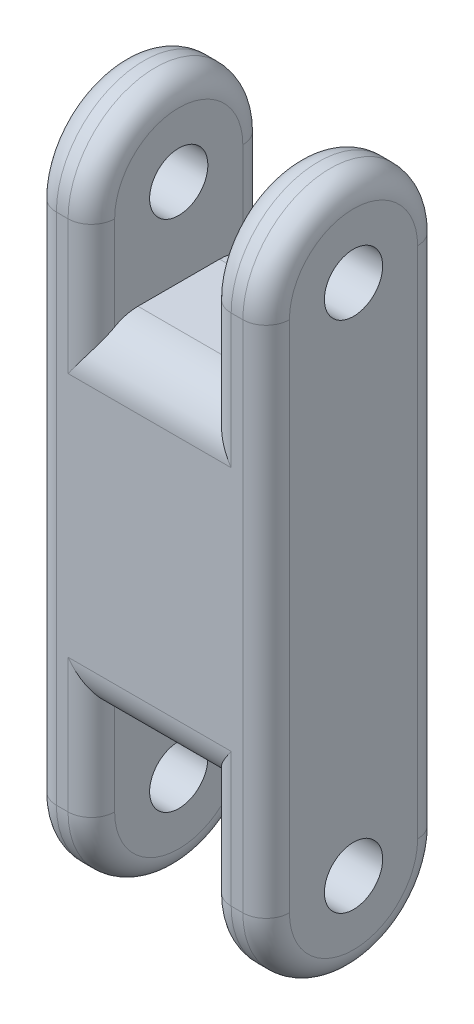
SolidWorks part; units mm, degrees
material "ABS"
ref_plane "Front" through (0, 0, 0) normal (0, 0, 1) x (1, 0, 0)
ref_plane "Top" through (0, 0, 0) normal (0, 1, 0) x (1, 0, 0)
ref_plane "Right" through (0, 0, 0) normal (1, 0, 0) x (0, 0, -1)
sketch "Sketch1" plane through (0, 0, 0) normal (1, 0, 0) x (0, 0, -1)
  line L0 (-4.7625, 0) -> (-4.7625, 27.9908)
  line L1 (4.7625, 27.9908) -> (4.7625, 0)
  arc A0 (-4.7625, 27.9908) -> (4.7625, 27.9908) centre (0, 27.9908) cw
  arc A1 (4.7625, 0) -> (-4.7625, 0) centre (0, 0) cw
  dimension "D1" = 9.525
  dimension "D2" = 27.9908
extrude "Boss-Extrude1" add sketch "Sketch1" along normal blind 12.7
sketch "Sketch2" plane through (12.7, 0, 0) normal (1, 0, 0) x (0, 0, -1)
  circle A0 centre (0, 0) radius 1.5875
  circle A1 centre (0, 27.9908) radius 1.5875
  dimension "D1" = 3.175
extrude "Cut-Extrude1" cut sketch "Sketch2" against normal blind 19.05
sketch3d "3DSketch1"
  line L0 (6.35, 27.9908, -4.7625) -> (6.35, 23.2283, -4.7625)
  line L1 (12.7, 27.9908, -4.7625) -> (0, 27.9908, -4.7625) construction
  line L2 (12.7, 27.9908, 4.7625) -> (0, 27.9908, 4.7625) construction
  line L3 (6.35, 27.9908, 4.7625) -> (6.35, 23.2283, 4.7625)
  line L5 (6.35, 0, 4.7625) -> (6.35, 4.7625, 4.7625)
  line L7 (12.7, 0, 4.7625) -> (0, 0, 4.7625) construction
  line L8 (12.7, 0, -4.7625) -> (0, 0, -4.7625) construction
  line L9 (6.35, 0, -4.7625) -> (6.35, 4.7625, -4.7625)
  line L10 (6.35, 23.2283, -4.7625) -> (6.35, 23.2283, 4.7625)
  line L11 (6.35, 4.7625, -4.7625) -> (6.35, 4.7625, 4.7625)
  arc A0 (6.35, 27.9908, -4.7625) -> (6.35, 27.9908, 4.7625) centre (6.35, 27.9908, 0) ccw
  arc A2 (6.35, 0, 4.7625) -> (6.35, 0, -4.7625) centre (6.35, 0, 0) ccw
  point P6 (11.1125, 27.9908, 0)
  point P18 (11.1125, 0, 0)
  dimension "D1" = 4.7625
  dimension "D2" = 4.7625
extrude "Cut-Extrude2" cut sketch "3DSketch1" along direction (-1, 0, 0) on the side against the normal mid plane 6.35
fillet "Fillet2" radius 2.54 4 edges
fillet "Fillet3" radius 1.27 20 edges at (0, 32.7533, 0) (0, 13.9954, -4.7625) (0, -4.7625, 0) (12.7, 32.7533, 0) (12.7, 13.9954, -4.7625) (12.7, -4.7625, 0) (0, 13.9954, 4.7625) (12.7, 13.9954, 4.7625)
sketch "Sketch3" plane through (0, 0, 0) normal (-1, 0, 0) x (0, 0, 1)
  line L0 (-3.4925, 27.9908) -> (-3.4925, 0) construction
  circle A0 centre (-2.2257, 2.096) radius 1.0868
  arc A2 (-3.4925, 0) -> (3.4925, 0) centre (0, 0) ccw construction
  dimension "D1" = 2.1736
  dimension "D2" = 1.2668
  dimension "D3" = 3.0573
extrude "Boss-Extrude2" add sketch "Sketch3" along normal blind 2.54
fillet "Fillet4" radius 0.762 1 edges at (-2.54, 2.096, -1.1389)
ref_plane "Plane1" through (0, 3.477, -2.0074) normal (0, 0.866, -0.5) x (-1, 0, 0)
sketch "Sketch4" plane through (0, 3.477, -2.0074) normal (0, 0.866, -0.5) x (-1, 0, 0)
  line L0 (0, 10.9708) -> (0, -3.0246) construction
  line L3 (-1.905, -4.1244) -> (-1.27, -4.1244) construction
  circle A0 centre (0.8566, -0.8068) radius 0.4916
  dimension "D1" = 0.8566
  dimension "D2" = 3.3177
  dimension "D3" = 0.9831
extrude "Cut-Extrude3" cut sketch "Sketch4" against normal blind 2.54
